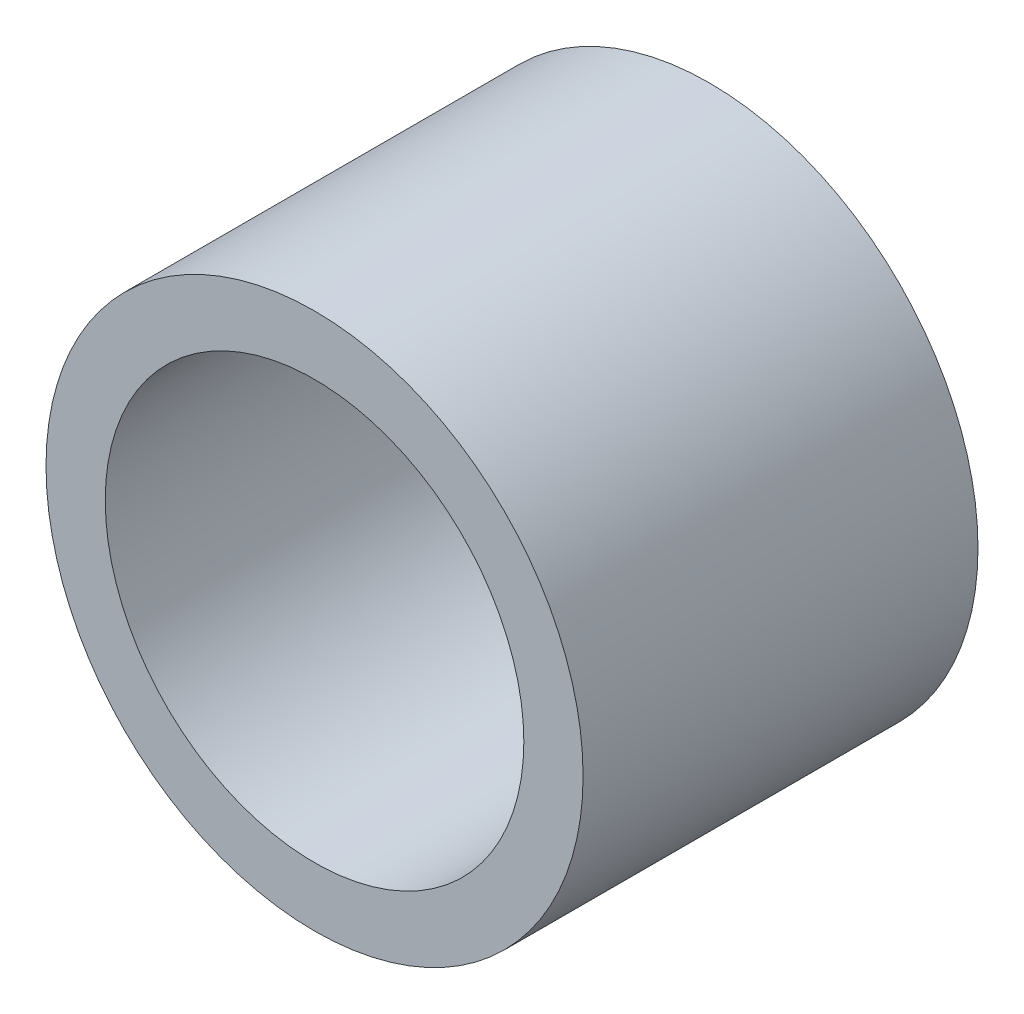
SolidWorks part; units mm, degrees
ref_plane "前视基准面" through (0, 0, 0) normal (0, 0, 1) x (1, 0, 0)
ref_plane "上视基准面" through (0, 0, 0) normal (0, 1, 0) x (1, 0, 0)
ref_plane "右视基准面" through (0, 0, 0) normal (1, 0, 0) x (0, 0, -1)
other "Configuration Table"
sketch "草图1" plane through (0, 0, 0) normal (0, 0, 1) x (1, 0, 0)
  circle A0 centre (0, 0) radius 2.65
  circle A1 centre (0, 0) radius 3.4
  dimension "D1" = 5.3
  dimension "D2" = 6.8
extrude "凸台-拉伸1" add sketch "草图1" along normal blind 5
